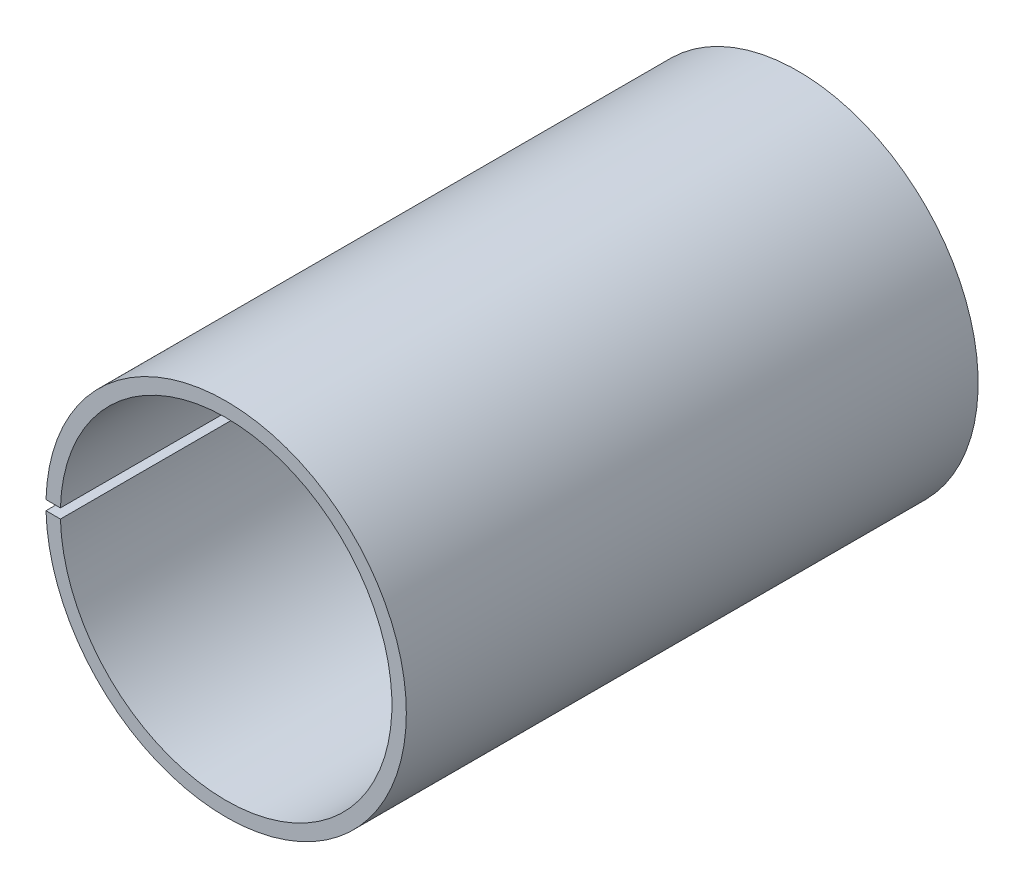
SolidWorks part; units mm, degrees
material "延性铁"
ref_plane "前视基准面" through (0, 0, 0) normal (0, 0, 1) x (1, 0, 0)
ref_plane "上视基准面" through (0, 0, 0) normal (0, 1, 0) x (1, 0, 0)
ref_plane "右视基准面" through (0, 0, 0) normal (1, 0, 0) x (0, 0, -1)
sketch "草图2" plane through (0, 0, 0) normal (0, 0, 1) x (1, 0, 0)
  circle A0 centre (0, 0) radius 34.5
  circle A1 centre (0, 0) radius 37.5
  dimension "D1" = 75
  dimension "D2" = 3
extrude "凸台-拉伸1" add sketch "草图2" along normal mid plane 119
sketch "草图3" plane through (0, 0, 0) normal (1, 0, 0) x (0, 0, -1)
  line L0 (0, 0) -> (69.648, 0) construction
  line L2 (59.5, -37.5) -> (59.5, 37.5) construction
  line L3 (44.5, -5) -> (59.5, -5)
  line L5 (44.5, 5) -> (59.5, 5)
  line L6 (59.5, -5) -> (59.5, 5)
  line L7 (44.5, -5) -> (59.5, 5) construction
  line L8 (44.5, 5) -> (59.5, -5) construction
  arc A0 (44.5, 5) -> (44.5, -5) centre (44.5, 0) ccw
  point P2 (52, 0)
  dimension "D2" = 5
  dimension "D1" = 15
extrude "切除-拉伸1" cut sketch "草图3" against normal up to next
sketch "草图4" plane through (0, 0, 0) normal (1, 0, 0) x (0, 0, -1)
  line L0 (-59.5, 37.5) -> (-59.5, -37.5) construction
  line L1 (59.5, 1) -> (-59.5, 1)
  line L2 (59.5, 1) -> (59.5, -1)
  line L3 (59.5, -1) -> (-59.5, -1)
  line L4 (-59.5, 1) -> (-59.5, -1)
  line L5 (59.5, 1) -> (-59.5, -1) construction
  line L6 (59.5, -1) -> (-59.5, 1) construction
  point P0 (0, 0)
  dimension "D1" = 2
extrude "切除-拉伸2" cut sketch "草图4" against normal up to next
